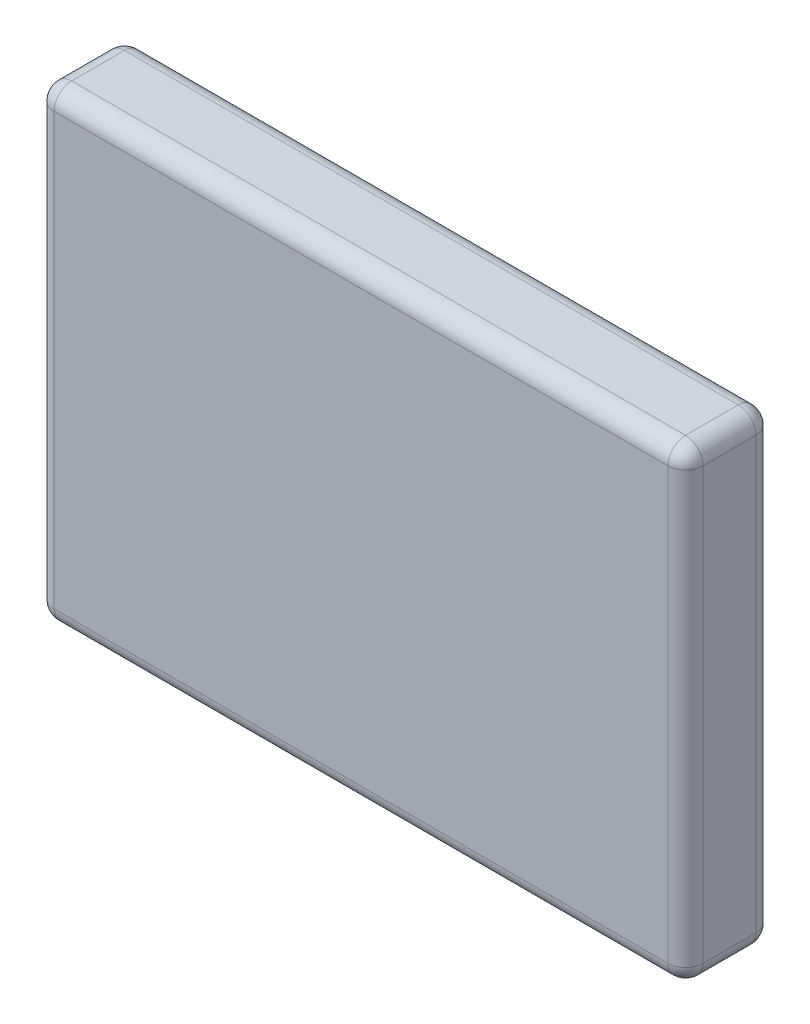
SolidWorks part; units mm, degrees
ref_plane "Front Plane" through (0, 0, 0) normal (0, 0, 1) x (1, 0, 0)
ref_plane "Top Plane" through (0, 0, 0) normal (0, 1, 0) x (1, 0, 0)
ref_plane "Right Plane" through (0, 0, 0) normal (1, 0, 0) x (0, 0, -1)
sketch "Sketch1" plane through (0, 0, 0) normal (0, 0, 1) x (1, 0, 0)
  line L1 (0, 0) -> (36.9, 0)
  line L2 (0, 0) -> (0, 26.5)
  line L3 (0, 26.5) -> (36.9, 26.5)
  line L4 (36.9, 0) -> (36.9, 26.5)
  dimension "D1" = 26.5
  dimension "D2" = 36.9
extrude "Boss-Extrude1" add sketch "Sketch1" along normal blind 5
fillet "Fillet1" radius 1 12 edges at (0, 13.25, 5) (0, 13.25, 0) (0, 0, 2.5) (18.45, 0, 5) (18.45, 0, 0) (18.45, 26.5, 5) (0, 26.5, 2.5) (18.45, 26.5, 0) (36.9, 0, 2.5) (36.9, 13.25, 5) (36.9, 26.5, 2.5) (36.9, 13.25, 0)
